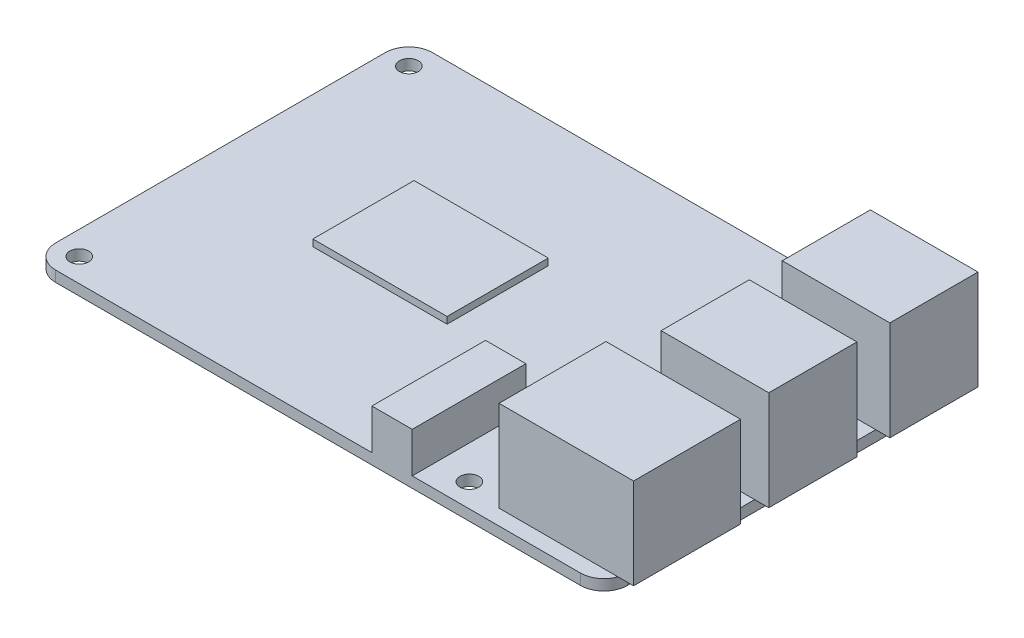
SolidWorks part; units mm, degrees
ref_plane "Front Plane" through (0, 0, 0) normal (0, 0, 1) x (1, 0, 0)
ref_plane "Top Plane" through (0, 0, 0) normal (0, 1, 0) x (1, 0, 0)
ref_plane "Right Plane" through (0, 0, 0) normal (1, 0, 0) x (0, 0, -1)
sketch "Sketch1" plane through (0, 0, 0) normal (0, 1, 0) x (1, 0, 0)
  line L0 (0, 47.4425) -> (0, -49.9071) construction
  line L1 (-83.5208, 0) -> (83.3839, 0) construction
  line L3 (-39, 28) -> (39, 28)
  line L4 (-42.5, 24.5) -> (-42.5, -24.5)
  line L5 (-39, -28) -> (39, -28)
  line L6 (42.5, 24.5) -> (42.5, -24.5)
  arc A0 (39, 28) -> (42.5, 24.5) centre (39, 24.5) cw
  arc A1 (42.5, -24.5) -> (39, -28) centre (39, -24.5) cw
  arc A2 (-39, -28) -> (-42.5, -24.5) centre (-39, -24.5) cw
  arc A3 (-42.5, 24.5) -> (-39, 28) centre (-39, 24.5) cw
  circle A4 centre (-39, 24.5) radius 1.4
  circle A5 centre (19, 24.5) radius 1.4
  circle A6 centre (19, -24.5) radius 1.4
  circle A7 centre (-39, -24.5) radius 1.4
  dimension "D3" = 3.5
  dimension "D4" = 2.8
  dimension "D5" = 2.8
  dimension "D1" = 56
  dimension "D2" = 85
  dimension "D6" = 23.5
  dimension "D7" = 3.5
extrude "Boss-Extrude1" add sketch "Sketch1" along normal blind 1.6
sketch "Sketch2" plane through (0, 1.6, 0) normal (0, 1, 0) x (1, 0, 0)
  line L0 (-39, -28) -> (39, -28) construction
  line L1 (24.6, -9.8) -> (44.6, -9.8)
  line L2 (24.6, -9.8) -> (24.6, -25.7)
  line L3 (24.6, -25.7) -> (44.6, -25.7)
  line L4 (44.6, -9.8) -> (44.6, -25.7)
  line L5 (42.5, -24.5) -> (42.5, 24.5) construction
  dimension "D1" = 2.3
  dimension "D2" = 15.9
  dimension "D3" = 2.1
  dimension "D4" = 20
extrude "Boss-Extrude2" add sketch "Sketch2" along normal blind 13.5
sketch "Sketch3" plane through (0, 1.6, 0) normal (0, 1, 0) x (1, 0, 0)
  line L0 (42.5, -9.8) -> (24.6, -9.8) construction
  line L1 (28.6, 7.5) -> (44.6, 7.5)
  line L2 (28.6, 7.5) -> (28.6, -5.6)
  line L3 (28.6, -5.6) -> (44.6, -5.6)
  line L4 (44.6, 7.5) -> (44.6, -5.6)
  line L5 (28.6, 25.5) -> (44.6, 25.5)
  line L6 (28.6, 25.5) -> (28.6, 12.4)
  line L7 (28.6, 12.4) -> (44.6, 12.4)
  line L8 (44.6, 25.5) -> (44.6, 12.4)
  line L9 (39, 28) -> (-39, 28) construction
  line L10 (44.6, -25.7) -> (44.6, -9.8) construction
  dimension "D1" = 13.1
  dimension "D2" = 13.1
  dimension "D3" = 4.2
  dimension "D4" = 4.9
  dimension "D5" = 2.5
  dimension "D6" = 16
  dimension "D7" = 16
extrude "Boss-Extrude3" add sketch "Sketch3" along normal blind 14.8
sketch "Sketch4" plane through (0, 1.6, 0) normal (0, 1, 0) x (1, 0, 0)
  line L0 (42.5, -9.8) -> (42.5, -5.6) construction
  line L1 (8, -11.1) -> (14, -11.1)
  line L2 (8, -11.1) -> (8, -28)
  line L3 (8, -28) -> (14, -28)
  line L4 (14, -11.1) -> (14, -28)
  line L5 (-39, -28) -> (39, -28) construction
  dimension "D1" = 6
  dimension "D2" = 28.5
  dimension "D3" = 0
  dimension "D4" = 16.9
extrude "Boss-Extrude4" add sketch "Sketch4" along normal blind 6
sketch "Sketch6" plane through (0, 1.6, 0) normal (0, 1, 0) x (1, 0, 0)
  line L1 (-22.8864, 9.1552) -> (-2.9394, 9.1552)
  line L2 (-22.8864, 9.1552) -> (-22.8864, -5.8818)
  line L3 (-22.8864, -5.8818) -> (-2.9394, -5.8818)
  line L4 (-2.9394, 9.1552) -> (-2.9394, -5.8818)
extrude "Boss-Extrude5" add sketch "Sketch6" along normal blind 1
